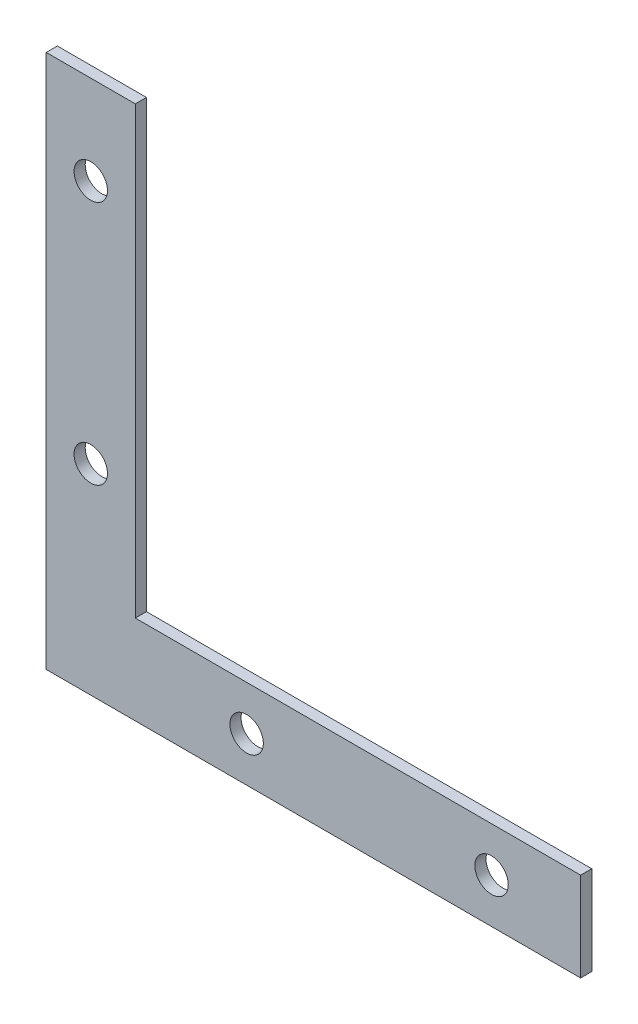
SolidWorks part; units mm, degrees
material "Galvanized Steel"
ref_plane "Front Plane" through (0, 0, 0) normal (0, 0, 1) x (1, 0, 0)
ref_plane "Top Plane" through (0, 0, 0) normal (0, 1, 0) x (1, 0, 0)
ref_plane "Right Plane" through (0, 0, 0) normal (1, 0, 0) x (0, 0, -1)
sketch "Sketch1" plane through (0, 0, 0) normal (0, 0, 1) x (1, 0, 0)
  line L0 (0, 0) -> (0, 76.2)
  line L1 (0, 76.2) -> (12.7, 76.2)
  line L2 (12.7, 76.2) -> (12.7, 12.7)
  line L3 (12.7, 12.7) -> (76.2, 12.7)
  line L4 (76.2, 12.7) -> (76.2, 0)
  line L5 (76.2, 0) -> (0, 0)
  line L6 (0, 0) -> (12.7, 12.7) construction
  circle A0 centre (63.5, 6.35) radius 2.3813
  circle A1 centre (28.575, 6.35) radius 2.3813
  circle A2 centre (6.35, 63.5) radius 2.3812
  circle A3 centre (6.35, 28.575) radius 2.3812
  dimension "D9" = 4.7625
  dimension "D10" = 4.7625
  dimension "D1" = 12.7
  dimension "D2" = 12.7
  dimension "D3" = 76.2
  dimension "D4" = 76.2
  dimension "D5" = 6.35
  dimension "D6" = 6.35
  dimension "D7" = 12.7
  dimension "D8" = 28.575
extrude "Boss-Extrude1" add sketch "Sketch1" along normal blind 1.5875
